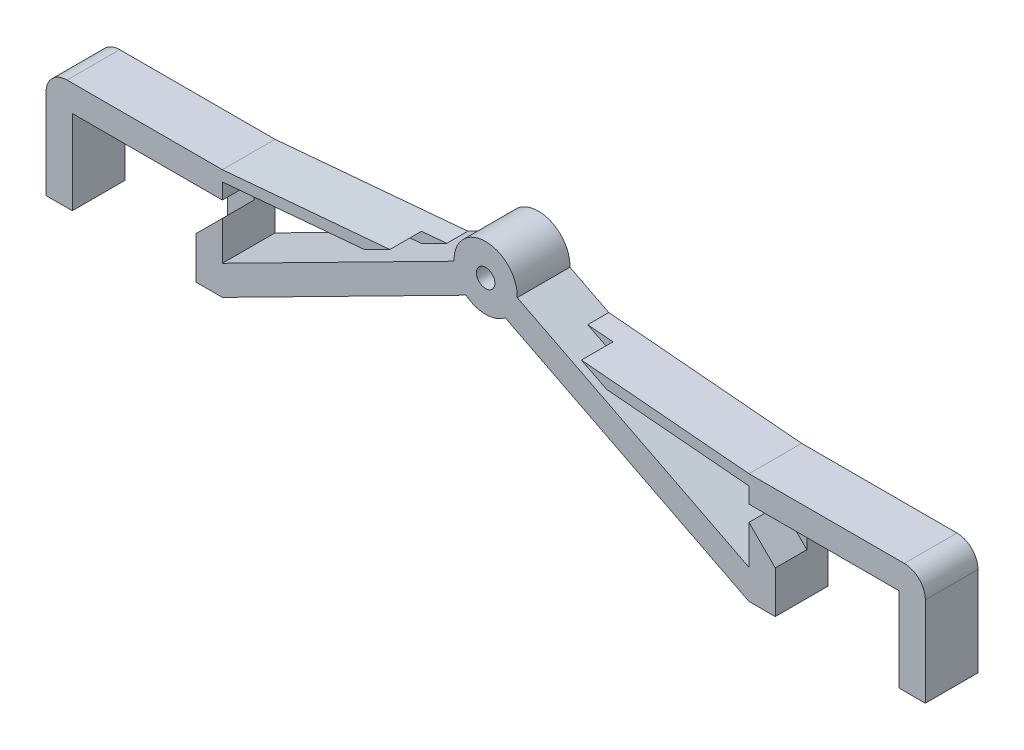
SolidWorks part; units mm, degrees
material "ABS"
ref_plane "Přední rovina" through (0, 0, 0) normal (0, 0, 1) x (1, 0, 0)
ref_plane "Horní rovina" through (0, 0, 0) normal (0, 1, 0) x (1, 0, 0)
ref_plane "Pravá rovina" through (0, 0, 0) normal (1, 0, 0) x (0, 0, -1)
sketch "Skica1" plane through (0, 0, 0) normal (0, 0, 1) x (1, 0, 0)
  line L0 (0, 0) -> (0, 16)
  line L1 (0, 16) -> (23.5, 16)
  line L2 (23.5, 16) -> (23.5, 0)
  line L3 (23.5, 0) -> (28.5, 0)
  line L4 (28.5, 0) -> (74.7688, 23.4973)
  line L5 (0, 0) -> (-5, 0)
  line L6 (-5, 0) -> (-5, 21)
  line L7 (-5, 21) -> (28.5, 21)
  line L8 (28.5, 21) -> (28.5, 5.6078)
  line L9 (28.5, 5.6078) -> (72.5048, 27.9554)
  line L10 (78.5, 31) -> (78.5, 25.3922) construction
  line L11 (78.5, 25.3922) -> (82.2312, 23.4973) construction
  line L12 (84.4952, 27.9554) -> (78.5, 31) construction
  line L13 (128.5, 5.6078) -> (84.4952, 27.9554)
  line L14 (72.5048, 27.9554) -> (78.5, 31) construction
  line L15 (78.5, 31) -> (78.5, 25.3922) construction
  line L16 (78.5, 25.3922) -> (74.7688, 23.4973) construction
  line L17 (78.5, 31) -> (78.5, 46.3264) construction
  line L18 (128.5, 21) -> (128.5, 5.6078)
  line L19 (78.5, 25.3922) -> (78.5, 12.6076) construction
  line L20 (162, 21) -> (128.5, 21)
  line L21 (162, 0) -> (162, 21)
  line L22 (157, 0) -> (162, 0)
  line L23 (128.5, 0) -> (82.2312, 23.4973)
  line L24 (133.5, 0) -> (128.5, 0)
  line L25 (133.5, 16) -> (133.5, 0)
  line L26 (157, 16) -> (133.5, 16)
  line L27 (157, 0) -> (157, 16)
  arc A0 (74.7688, 23.4973) -> (82.2312, 23.4973) centre (78.5, 28.1961) ccw
  arc A1 (84.4952, 27.9554) -> (72.5048, 27.9554) centre (78.5, 28.1961) ccw
  circle A2 centre (78.5, 28.1961) radius 1.75
  dimension "D11" = 12
  dimension "D12" = 3.5
  dimension "D1" = 5
  dimension "D2" = 5
  dimension "D3" = 23.5
  dimension "D4" = 16
  dimension "D5" = 5
  dimension "D6" = 5
  dimension "D7" = 5
  dimension "D8" = 55
  dimension "D9" = 10
extrude "Přidat vysunutím1" add sketch "Skica1" along normal mid plane 10
fillet "Zaoblit1" radius 4 2 edges at (-5, 21, 0) (162, 21, 0)
sketch "Skica2" plane through (0, 0, 0) normal (0, 0, 1) x (1, 0, 0)
  line L0 (28.5, 21) -> (65.1171, 24.2036)
  line L1 (72.5048, 27.9554) -> (28.5, 5.6078) construction
  line L2 (65.1171, 24.2036) -> (60.341, 21.7781)
  line L3 (60.341, 21.7781) -> (28.5, 18.9924)
  line L4 (28.5, 5.6078) -> (28.5, 21) construction
  line L5 (28.5, 18.9924) -> (28.5, 21)
  line L6 (28.5, 21) -> (-1, 21) construction
  dimension "D1" = 2
  dimension "D2" = 175
extrude "Přidat vysunutím2" add sketch "Skica2" along normal mid plane 10
ref_plane "Rovina1" through (78.5, 0, 0) normal (-1, 0, 0) x (0, 0, 1)
mirror "Zrcadlit1" about plane through (78.5, 0, 0) normal (-1, 0, 0) of "Přidat vysunutím2"
sketch "Skica3" plane through (0, 0, 0) normal (0, -1, 0) x (1, 0, 0)
  line L0 (11.75, -5) -> (11.75, 5) construction
  line L1 (0, -5) -> (23.5, -5) construction
  line L2 (0, 5) -> (23.5, 5) construction
  line L5 (11.75, 0) -> (-1.75, 0) construction
  line L6 (11.75, 0) -> (25.25, 0) construction
  circle A0 centre (-1.75, 0) radius 1.05
  circle A1 centre (25.25, 0) radius 1.05
  dimension "D1" = 2.1
  dimension "D2" = 27
extrude "Odebrat vysunutím1" cut sketch "Skica3" against normal blind 6
mirror "Zrcadlit2" about plane through (78.5, 0, 0) normal (-1, 0, 0) of "Odebrat vysunutím1"
sketch "Skica4" plane through (0, 0, 5) normal (0, 0, 1) x (1, 0, 0)
  line L0 (23.5, 16) -> (28.5, 16)
  line L1 (28.5, 5.6078) -> (28.5, 18.9924) construction
  line L2 (28.5, 16) -> (28.5, 13)
  line L3 (28.5, 13) -> (23.5, 8)
  line L4 (23.5, 16) -> (23.5, 0) construction
  line L5 (23.5, 8) -> (23.5, 16)
  dimension "D1" = 45
  dimension "D2" = 3
  dimension "D3" = 8
extrude "Odebrat vysunutím2" cut sketch "Skica4" against normal blind 6
mirror "Zrcadlit3" about plane through (78.5, 0, 0) normal (-1, 0, 0) of "Odebrat vysunutím2"
sketch "Skica5" plane through (0, 0, 5) normal (0, 0, 1) x (1, 0, 0)
  line L0 (60.341, 21.7781) -> (65.1171, 24.2036)
  line L1 (65.1171, 24.2036) -> (60.3145, 23.7834)
  line L2 (65.1171, 24.2036) -> (28.5, 21) construction
  line L3 (60.3145, 23.7834) -> (55.5384, 21.3579)
  line L4 (28.5, 18.9924) -> (60.341, 21.7781) construction
  line L5 (55.5384, 21.3579) -> (60.341, 21.7781)
  line L6 (91.8829, 24.2036) -> (96.6855, 23.7834)
  line L7 (91.8829, 24.2036) -> (128.5, 21) construction
  line L8 (101.4616, 21.3579) -> (96.659, 21.7781)
  line L9 (128.5, 18.9924) -> (96.659, 21.7781) construction
  line L10 (101.4616, 21.3579) -> (96.6855, 23.7834)
  line L11 (96.659, 21.7781) -> (91.8829, 24.2036)
  dimension "D1" = 1.8
  dimension "D2" = 1.8
extrude "Odebrat vysunutím3" cut sketch "Skica5" against normal up to surface (6 mm away) up to face at (26, 13.25, -1)
scale "Scale1" scale about centroid uniform scaling yes scale factor 8
